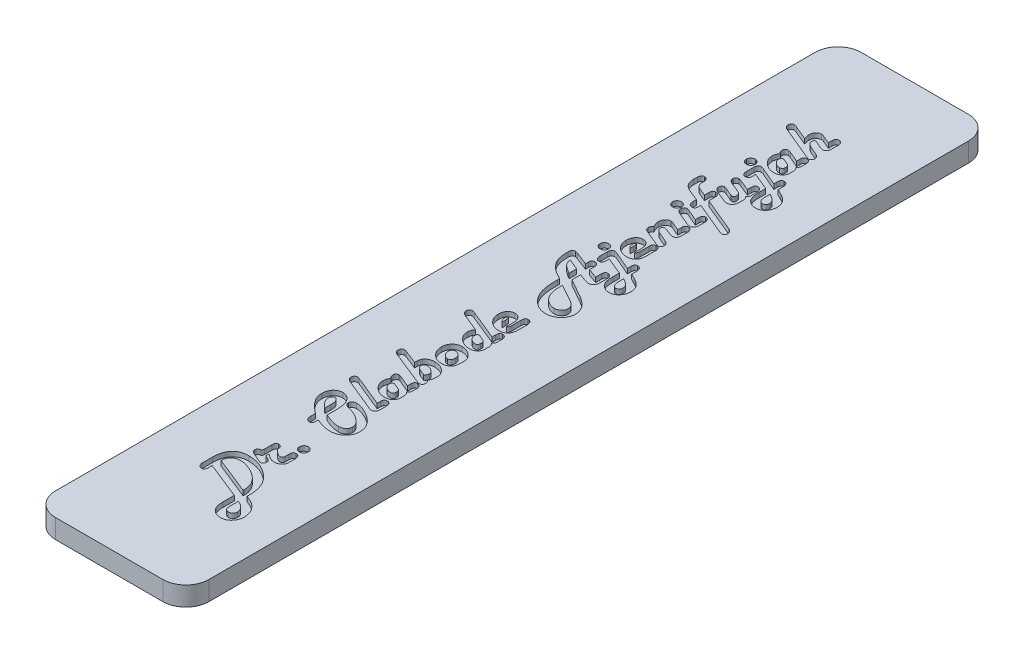
SolidWorks part; units mm, degrees
ref_plane "Front Plane" through (0, 0, 0) normal (0, 0, 1) x (1, 0, 0)
ref_plane "Top Plane" through (0, 0, 0) normal (0, 1, 0) x (1, 0, 0)
ref_plane "Right Plane" through (0, 0, 0) normal (1, 0, 0) x (0, 0, -1)
sketch "Sketch1" plane through (0, 0, 0) normal (0, 0, 1) x (1, 0, 0)
  line L0 (0, 1.5875) -> (0, -1.5875)
  line L1 (-12.7, 0) -> (12.7, 0) construction
  point P6 (0, 0)
  dimension "Width" = 25.4
  dimension "Thk" = 3.175
sketch "Sketch2" plane through (0, 0, 0) normal (1, 0, 0) x (0, 0, -1)
  line L0 (66.675, 0) -> (-66.675, 0)
  point P4 (0, 0)
  dimension "Length" = 133.35
sketch "Sketch3" plane through (0, 0, 0) normal (0, 0, 1) x (1, 0, 0)
  line L1 (12.7, 1.5875) -> (-12.7, 1.5875)
  line L2 (12.7, 1.5875) -> (12.7, -1.5875)
  line L3 (12.7, -1.5875) -> (-12.7, -1.5875)
  line L4 (-12.7, 1.5875) -> (-12.7, -1.5875)
  line L5 (12.7, 1.5875) -> (-12.7, -1.5875) construction
  line L6 (12.7, -1.5875) -> (-12.7, 1.5875) construction
  point P0 (0, 0)
extrude "Boss-Extrude1" add sketch "Sketch3" along normal up to vertex (66.675 mm away) and the other way up to vertex (66.675 mm away) up to point (0, 0, 66.675) other way up to point (0, 0, -66.675)
sketch "Sketch5" plane through (0, 1.5875, 0) normal (0, 1, 0) x (1, 0, 0)
  line L2 (9.652, -66.675) -> (-9.398, -66.675) construction
  line L3 (-12.7, -63.5025) -> (-12.7, 63.627) construction
  line L12 (12.7, -66.675) -> (12.7, 66.675)
  line L13 (12.7, 66.675) -> (-12.7, 66.675)
  line L14 (-12.7, 66.675) -> (-12.7, -66.675)
  line L15 (-12.7, -66.675) -> (12.7, -66.675)
  line L16 (12.7, -62.865) -> (12.7, 62.865)
  line L17 (8.89, 66.675) -> (-8.89, 66.675)
  line L18 (-12.7, 62.865) -> (-12.7, -62.865)
  line L19 (-8.89, -66.675) -> (8.89, -66.675)
  arc A8 (12.7, 62.865) -> (8.89, 66.675) centre (8.89, 62.865) ccw
  arc A9 (-8.89, 66.675) -> (-12.7, 62.865) centre (-8.89, 62.865) ccw
  arc A10 (12.7, -62.865) -> (8.89, -66.675) centre (8.89, -62.865) cw
  arc A11 (-8.89, -66.675) -> (-12.7, -62.865) centre (-8.89, -62.865) cw
  dimension "D2" = 3.81
  dimension "D1" = 0
extrude "Cut-Extrude2" cut sketch "Sketch5" against normal through all flip side to cut
sketch "Sketch4" plane through (0, 1.5875, 0) normal (0, 1, 0) x (1, 0, 0)
  line L0 (0, 0) -> (2.54, 0) construction
  line L1 (2.54, -66.675) -> (2.54, 66.675) construction
  line L2 (8.89, 66.675) -> (-8.89, 66.675) construction
  text T0 "Dr. Olabode Ajenifujah" font "Harlow Solid Italic" height in points 28
  point P8 (2.54, 0)
  dimension "D1" = 2.54
extrude "Cut-Extrude1" cut sketch "Sketch4" against normal blind 0.7937
